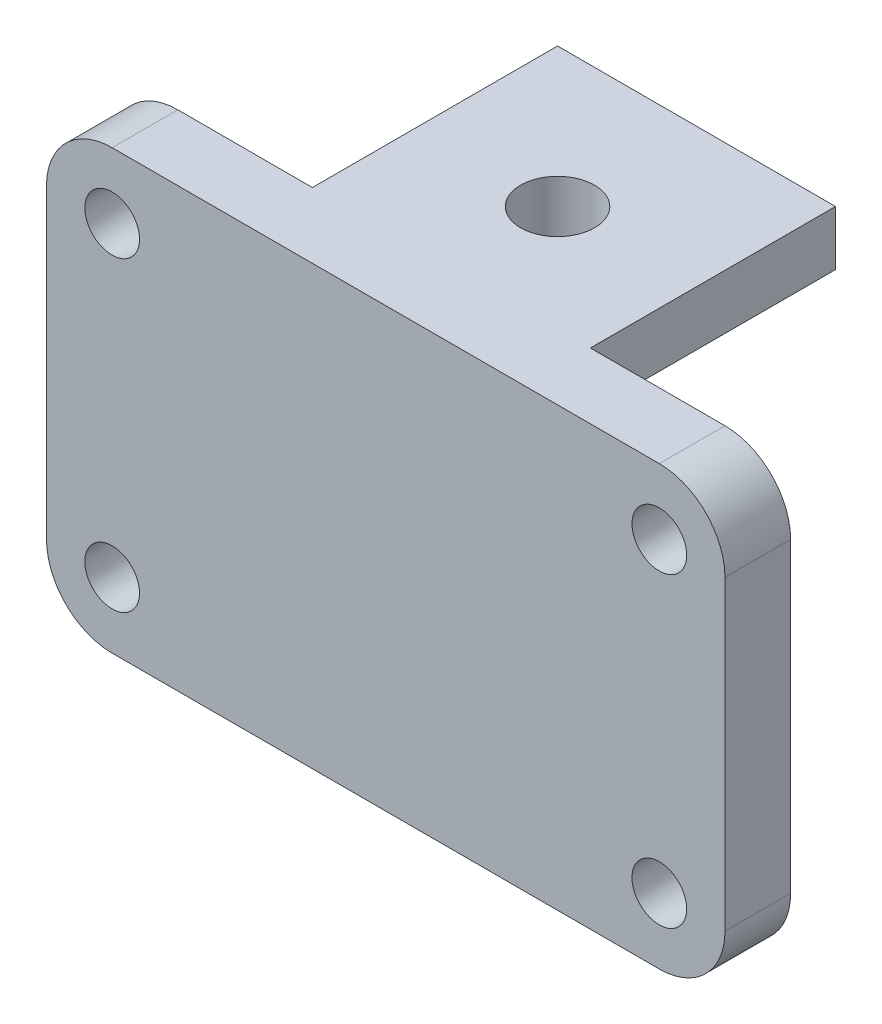
SolidWorks part; units mm, degrees
ref_plane "Front Plane" through (0, 0, 0) normal (0, 0, 1) x (1, 0, 0)
ref_plane "Top Plane" through (0, 0, 0) normal (0, 1, 0) x (1, 0, 0)
ref_plane "Right Plane" through (0, 0, 0) normal (1, 0, 0) x (0, 0, -1)
sketch "Sketch1" plane through (0, 0, 0) normal (0, 1, 0) x (1, 0, 0)
  line L1 (-12.7, 12.7) -> (12.7, 12.7)
  line L2 (-12.7, 12.7) -> (-12.7, -12.7)
  line L3 (-12.7, -12.7) -> (12.7, -12.7)
  line L4 (12.7, 12.7) -> (12.7, -12.7)
  line L5 (-12.7, 12.7) -> (12.7, -12.7) construction
  line L6 (-12.7, -12.7) -> (12.7, 12.7) construction
  point P0 (0, 0)
  dimension "D1" = 25.4
  dimension "D2" = 25.4
extrude "Boss-Extrude1" add sketch "Sketch1" along normal blind 5
hole_wizard "1/4 Clearance Hole1" positions "Sketch2" profile "Sketch3" hole size "1/4" standard "ANSI Inch" end condition through all
sketch "Sketch2" plane through (0, 5, 0) normal (0, 1, 0) x (1, 0, 0)
  point P0 (0, 0)
sketch "Sketch3" plane through (0, 5, 0) normal (1, 0, 0) x (0, 0, 1)
  line L0 (0, 0) -> (0, 5)
  line L1 (0, 5) -> (3.3782, 5)
  line L2 (3.3782, 5) -> (3.3782, 0)
  line L5 (3.3782, 0) -> (0, 0)
  line L11 (0, -6.35) -> (0, 107.95) construction
  dimension "Thru Hole Dia." = 6.7564
  dimension "Thru Hole Depth" = 5
sketch "Sketch4" plane through (0, 0, 12.7) normal (0, 0, 1) x (1, 0, 0)
  line L0 (-31, -35) -> (-31, 5)
  line L1 (-25, -29) -> (25, -29) construction
  line L2 (-25, -29) -> (-25, -1) construction
  line L3 (-25, -1) -> (25, -1) construction
  line L4 (25, -29) -> (25, -1) construction
  line L5 (-25, -29) -> (25, -1) construction
  line L6 (-25, -1) -> (25, -29) construction
  line L7 (-31, 5) -> (31, 5)
  line L8 (31, -35) -> (31, 5)
  line L9 (-31, -35) -> (31, -35)
  line L10 (-12.7, 5) -> (12.7, 5) construction
  circle A0 centre (-25, -1) radius 2.5
  circle A1 centre (25, -1) radius 2.5
  circle A2 centre (25, -29) radius 2.5
  circle A3 centre (-25, -29) radius 2.5
  point P0 (0, -15)
  line M9 (-12.7, 0) -> (12.7, 0)
  line M10 (12.7, 0) -> (12.7, 5)
  line M11 (12.7, 5) -> (-12.7, 5)
  line M12 (-12.7, 5) -> (-12.7, 0)
  dimension "D4" = 5
  dimension "D1" = 6
  dimension "D2" = 50
  dimension "D3" = 28
extrude "Boss-Extrude2" add sketch "Sketch4" against normal mid plane 6 contours L0 L9 L8 L7 A3 A2 A1 A0 M10 M9 M12 | M12 M9 M10 M11
fillet "Fillet1" radius 6 4 edges at (31, -35, 12.7) (-31, -35, 12.7) (31, 5, 12.7) (-31, 5, 12.7)
